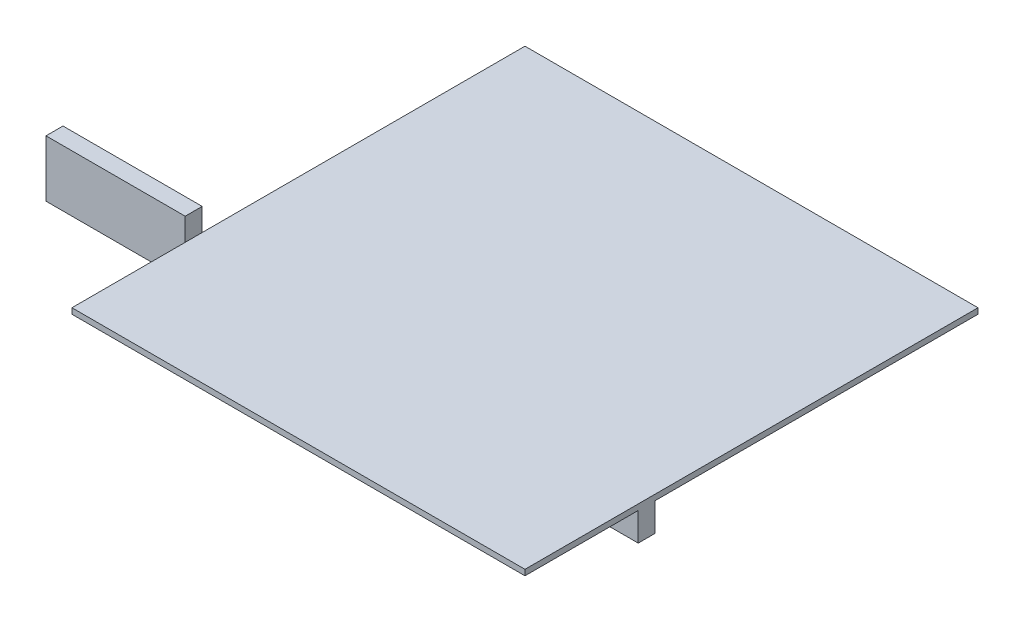
SolidWorks part; units mm, degrees
ref_plane "Front Plane" through (0, 0, 0) normal (0, 0, 1) x (1, 0, 0)
ref_plane "Top Plane" through (0, 0, 0) normal (0, 1, 0) x (1, 0, 0)
ref_plane "Right Plane" through (0, 0, 0) normal (1, 0, 0) x (0, 0, -1)
sketch "Sketch1" plane through (0, 0, 0) normal (0, 0, 1) x (1, 0, 0)
  line L0 (15.5538, 1.3278) -> (15.5538, 6.3278)
  line L1 (-9.0262, 6.3278) -> (15.5538, 6.3278)
  line L2 (-9.0262, 6.3278) -> (-9.0262, -3.6722)
  line L3 (-9.0262, -3.6722) -> (5.2381, -3.6722)
  line L6 (-9.0262, -3.6722) -> (15.5538, 6.3278) construction
  line L9 (15.5538, 1.3278) -> (95.5538, 1.3278)
  line L11 (5.2381, -3.6722) -> (95.5538, -3.6722)
  line L12 (95.5538, -3.6722) -> (95.5538, 1.3278)
  point P0 (0, 0)
  point P8 (0, 0)
  point P9 (15.5538, -3.6722)
  dimension "D1" = 24.58
  dimension "D2" = 10
  dimension "D3" = 5
  dimension "D4" = 80
extrude "Boss-Extrude3" add sketch "Sketch1" along normal blind 3
sketch "Sketch4" plane through (0, 1.3278, 0) normal (0, 1, 0) x (1, 0, 0)
  line L0 (95.5538, -3) -> (15.5538, -3) construction
  line L1 (15.5538, 57) -> (95.5538, 57)
  line L2 (15.5538, 57) -> (15.5538, -23)
  line L3 (15.5538, -23) -> (95.5538, -23)
  line L4 (95.5538, 57) -> (95.5538, -23)
  line L5 (15.5538, 57) -> (95.5538, -23) construction
  line L6 (15.5538, -23) -> (95.5538, 57) construction
  line L7 (95.5538, -3) -> (95.5538, 0) construction
  point P0 (55.5538, 17)
  dimension "D1" = 20
  dimension "D2" = 80
  dimension "D3" = 80
extrude "Boss-Extrude4" add sketch "Sketch4" along normal blind 1
